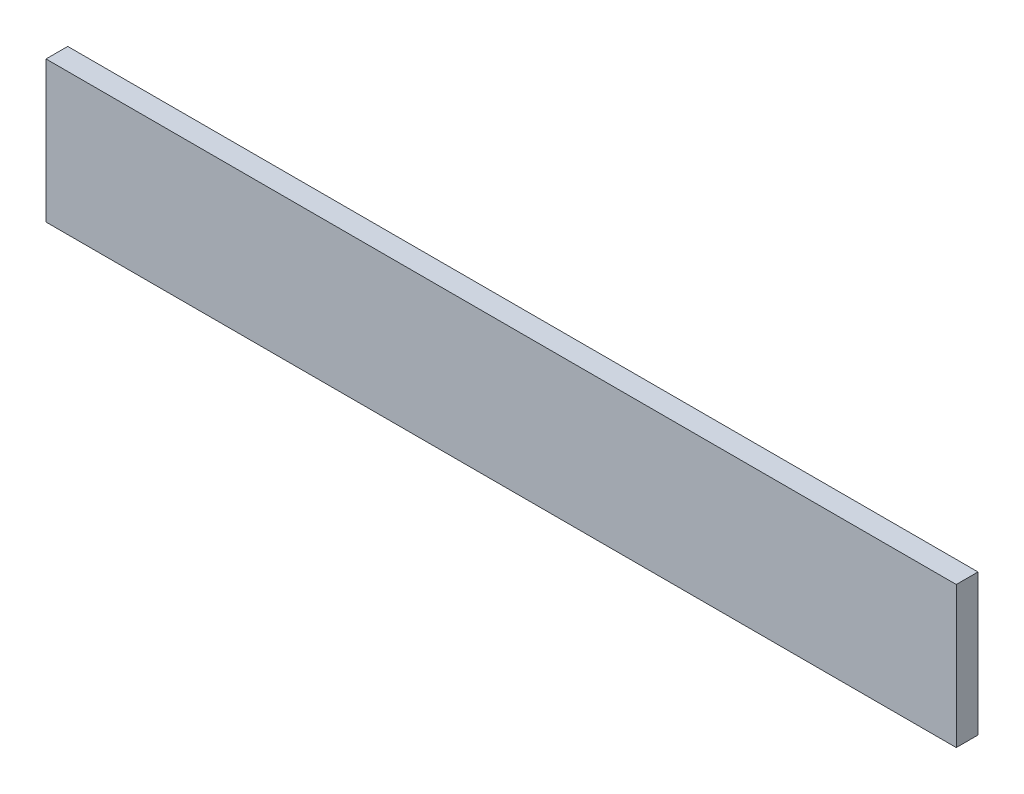
SolidWorks part; units mm, degrees
ref_plane "Plan de face" through (0, 0, 0) normal (0, 0, 1) x (1, 0, 0)
ref_plane "Plan de dessus" through (0, 0, 0) normal (0, 1, 0) x (1, 0, 0)
ref_plane "Plan de droite" through (0, 0, 0) normal (1, 0, 0) x (0, 0, -1)
sketch "Esquisse1" plane through (0, 0, 0) normal (0, 0, 1) x (1, 0, 0)
  line L1 (-265.9581, 41.275) -> (265.9581, 41.275)
  line L2 (-265.9581, 41.275) -> (-265.9581, -41.275)
  line L3 (-265.9581, -41.275) -> (265.9581, -41.275)
  line L4 (265.9581, 41.275) -> (265.9581, -41.275)
  line L5 (-265.9581, 41.275) -> (265.9581, -41.275) construction
  line L6 (-265.9581, -41.275) -> (265.9581, 41.275) construction
  point P0 (0, 0)
  dimension "D1" = 82.55
  dimension "D2" = 531.9161
extrude "Boss.-Extru.1" add sketch "Esquisse1" along normal blind 12.7
